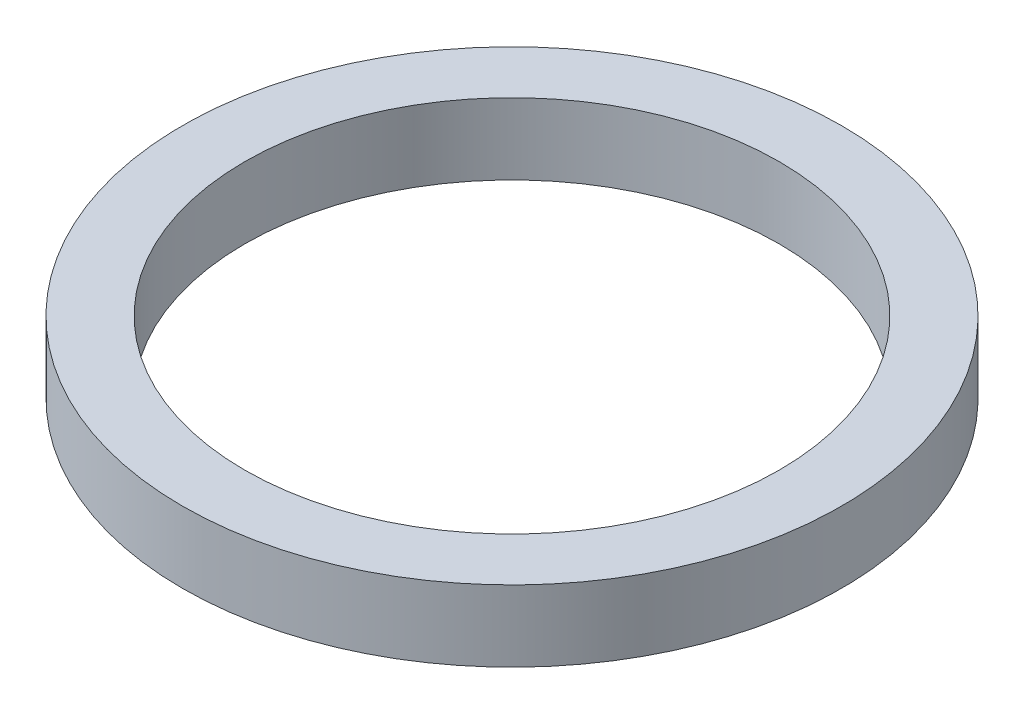
SolidWorks part; units mm, degrees
material "铸造不锈钢"
ref_plane "前视基准面" through (0, 0, 0) normal (0, 0, 1) x (1, 0, 0)
ref_plane "上视基准面" through (0, 0, 0) normal (0, 1, 0) x (1, 0, 0)
ref_plane "右视基准面" through (0, 0, 0) normal (1, 0, 0) x (0, 0, -1)
other "Configuration Table"
sketch "草图1" plane through (0, 0, 0) normal (0, 1, 0) x (1, 0, 0)
  circle A0 centre (0, 0) radius 15
  circle A1 centre (0, 0) radius 18.5
  dimension "D1" = 30
  dimension "D2" = 37
extrude "凸台-拉伸1" add sketch "草图1" along normal blind 4
